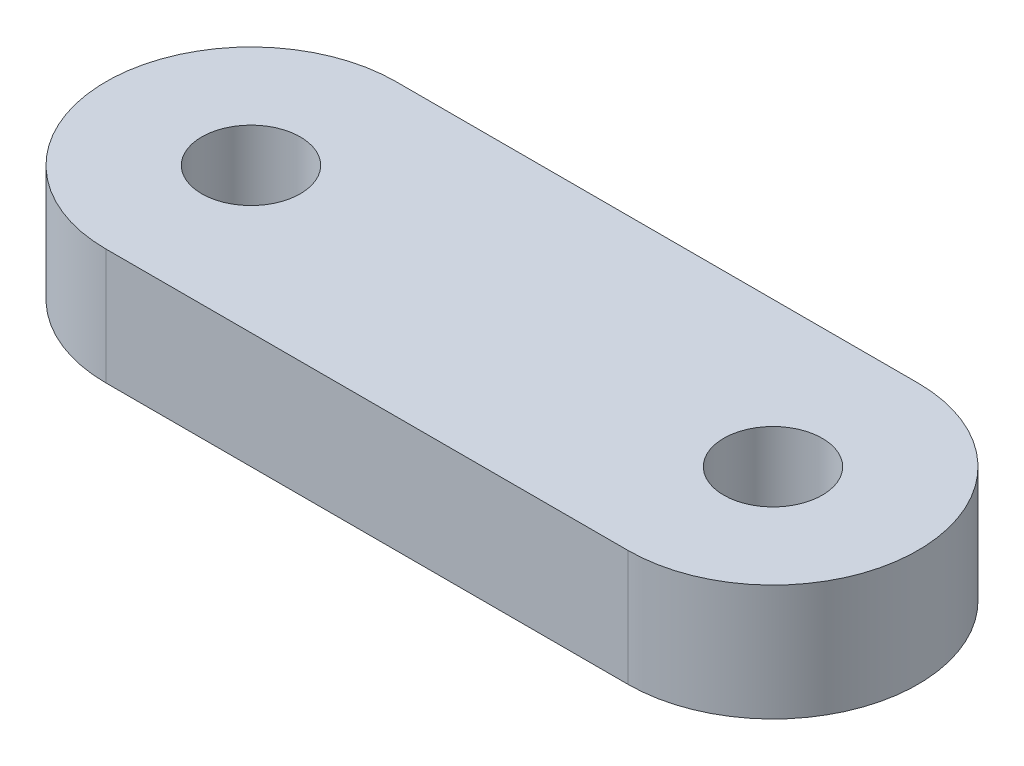
SolidWorks part; units mm, degrees
ref_plane "Front Plane" through (0, 0, 0) normal (0, 0, 1) x (1, 0, 0)
ref_plane "Top Plane" through (0, 0, 0) normal (0, 1, 0) x (1, 0, 0)
ref_plane "Right Plane" through (0, 0, 0) normal (1, 0, 0) x (0, 0, -1)
sketch "Sketch1" plane through (0, 0, 0) normal (0, 1, 0) x (1, 0, 0)
  line L1 (-9, 5) -> (9, 5)
  line L2 (-9, 5) -> (-9, -5) construction
  line L3 (-9, -5) -> (9, -5)
  line L4 (9, 5) -> (9, -5) construction
  line L5 (-9, 5) -> (9, -5) construction
  line L6 (-9, -5) -> (9, 5) construction
  arc A0 (9, -5) -> (9, 5) centre (9, 0) ccw
  arc A1 (-9, 5) -> (-9, -5) centre (-9, 0) ccw
  circle A2 centre (-9, 0) radius 1.7
  circle A3 centre (9, 0) radius 1.7
  point P0 (0, 0)
  dimension "D3" = 3.4
  dimension "D4" = 3.4
  dimension "D1" = 18
  dimension "D2" = 10
extrude "Boss-Extrude1" add sketch "Sketch1" along normal blind 4
equation "\"D4@Sketch1\" = \"D3@Sketch1\""
